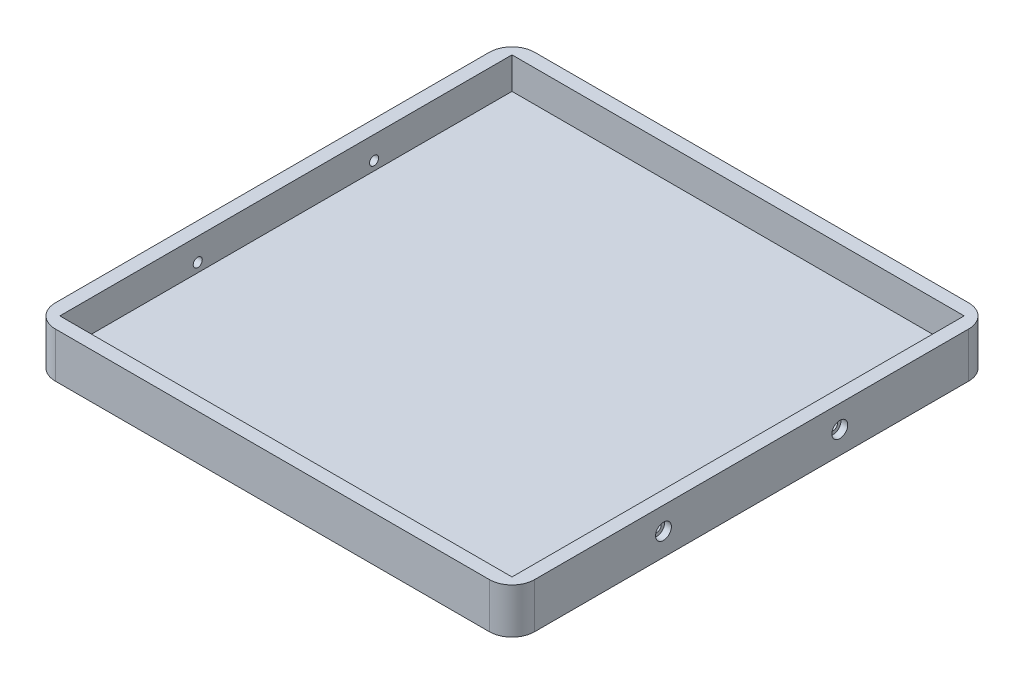
SolidWorks part; units mm, degrees
ref_plane "Front Plane" through (0, 0, 0) normal (0, 0, 1) x (1, 0, 0)
ref_plane "Top Plane" through (0, 0, 0) normal (0, 1, 0) x (1, 0, 0)
ref_plane "Right Plane" through (0, 0, 0) normal (1, 0, 0) x (0, 0, -1)
sketch "Sketch1" plane through (0, 0, 0) normal (0, 1, 0) x (1, 0, 0)
  line L1 (-53, 53) -> (53, 53)
  line L2 (-53, 53) -> (-53, -53)
  line L3 (-53, -53) -> (53, -53)
  line L4 (53, 53) -> (53, -53)
  line L5 (-53, 53) -> (53, -53) construction
  line L6 (-53, -53) -> (53, 53) construction
  point P0 (0, 0)
  dimension "D1" = 106
  dimension "D2" = 106
extrude "Boss-Extrude1" add sketch "Sketch1" along normal blind 10
sketch "Sketch3" plane through (0, 10, 0) normal (0, 1, 0) x (1, 0, 0)
  line L5 (-50, 50) -> (50, 50)
  line L6 (-50, 50) -> (-50, -50)
  line L7 (-50, -50) -> (50, -50)
  line L8 (50, 50) -> (50, -50)
  point P0 (0, 0)
  point P6 (0, 0)
extrude "Cut-Extrude5" cut sketch "Sketch3" against normal blind 7
sketch "Sketch7" plane through (0, 3, 0) normal (0, 1, 0) x (1, 0, 0)
  line L0 (0, 49) -> (0, 20.5) construction
  line L1 (-49, 49) -> (49, 49) construction
  line L2 (-49, 49) -> (-49, -49) construction
  line L3 (-49, -49) -> (49, -49) construction
  line L4 (49, 49) -> (49, -49) construction
  line L5 (0, -49) -> (0, -20.5) construction
  line L6 (49, -20.5) -> (19, -20.5)
  circle A0 centre (0, 20.5) radius 14.25
  circle A1 centre (19, -20.5) radius 14.25
  circle A2 centre (-19, -20.5) radius 14.25
  point P0 (0, 0)
  dimension "D1" = 28.5
  dimension "D2" = 28.5
sketch "Sketch8" plane through (0, 3, 0) normal (0, 1, 0) x (1, 0, 0)
  line L1 (-49, 49) -> (49, 49) construction
  line L2 (-49, 49) -> (-49, -49) construction
  line L3 (-49, -49) -> (49, -49) construction
  line L4 (49, 49) -> (49, -49) construction
  point P0 (0, 0)
  dimension "D1" = 98
  dimension "D2" = 98
sketch "Sketch12" plane through (53, 0, 0) normal (1, 0, 0) x (0, 0, -1)
  line L0 (-39, 10) -> (-39, 0)
  line L1 (-53, 10) -> (53, 10) construction
  line L2 (-39, 13) -> (-39, 3) construction
  line L3 (-53, 0) -> (53, 0) construction
  line L4 (39, 10) -> (39, 0)
  line L5 (39, 3) -> (39, 13) construction
  line L6 (-39, 10) -> (0, 10)
  line L7 (0, 10) -> (0, 0)
  line L8 (0, 10) -> (39, 10)
  line L9 (-19.5, 10) -> (-19.5, 0)
  line L10 (19.5, 10) -> (19.5, 0)
  circle A0 centre (-19.5, 5) radius 1.75
  circle A1 centre (19.5, 5) radius 1.75
  dimension "D1" = 3.5
extrude "Cut-Extrude9" cut sketch "Sketch12" against normal blind 1.5 contours L9 A0 | A1 L10 | A1 L10
sketch "Sketch14" plane through (51.5, 0, 0) normal (1, 0, 0) x (0, 0, -1)
  circle A0 centre (-19.5, 5) radius 1
  circle A1 centre (19.5, 5) radius 1
extrude "Cut-Extrude10" cut sketch "Sketch14" against normal blind 115.5 contours A0 | A1
sketch "Sketch15" plane through (-53, 0, 0) normal (-1, 0, 0) x (0, 0, 1)
  circle A0 centre (-19.5, 5) radius 1.75
  circle A1 centre (19.5, 5) radius 1.75
  dimension "D1" = 3.5
  dimension "D2" = 3.5
extrude "Cut-Extrude11" cut sketch "Sketch15" against normal blind 1.5 contours A0 | A1
fillet "Fillet1" radius 5 4 edges at (-53, 5, -53) (-53, 5, 53) (53, 5, 53) (53, 5, -53)
